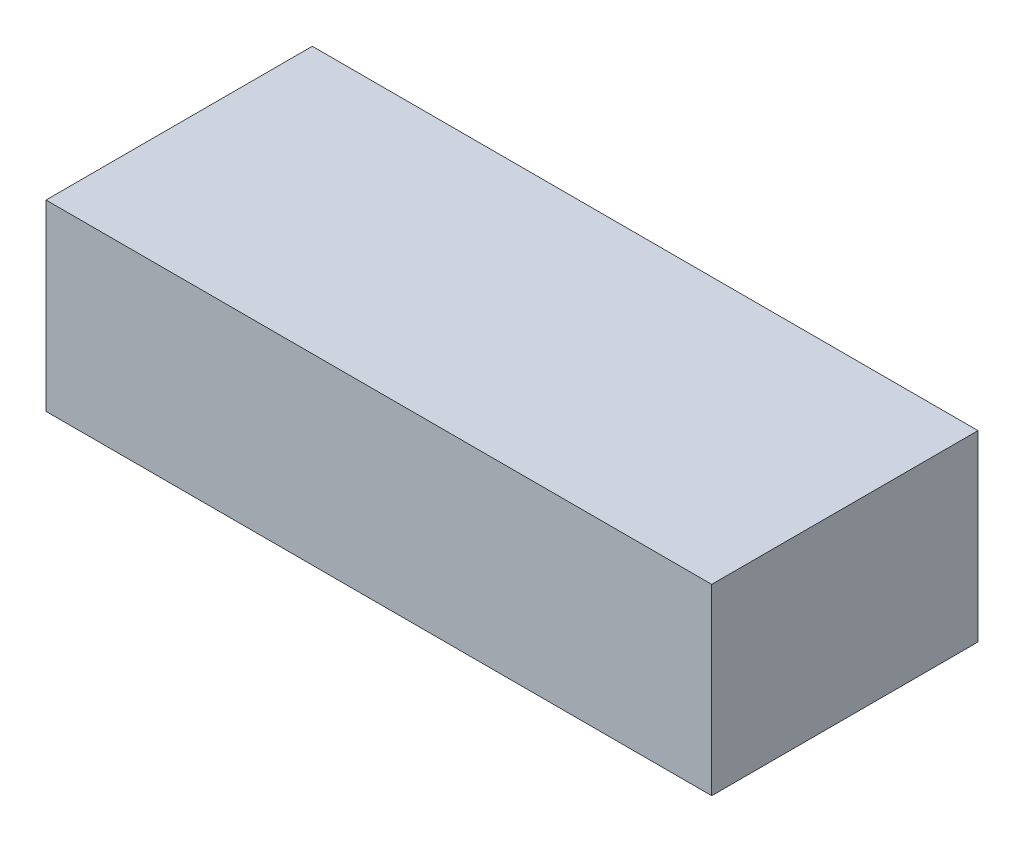
SolidWorks part; units mm, degrees
ref_plane "Front Plane" through (0, 0, 0) normal (0, 0, 1) x (1, 0, 0)
ref_plane "Top Plane" through (0, 0, 0) normal (0, 1, 0) x (1, 0, 0)
ref_plane "Right Plane" through (0, 0, 0) normal (1, 0, 0) x (0, 0, -1)
sketch "Sketch1" plane through (0, 0, 0) normal (0, 0, 1) x (1, 0, 0)
  line L1 (0, 0) -> (25.4, 0)
  line L2 (0, 0) -> (0, -6.985)
  line L3 (0, -6.985) -> (25.4, -6.985)
  line L4 (25.4, 0) -> (25.4, -6.985)
  dimension "D1" = 25.4
  dimension "D2" = 6.985
extrude "Extrude1" add sketch "Sketch1" along normal blind 10.16
